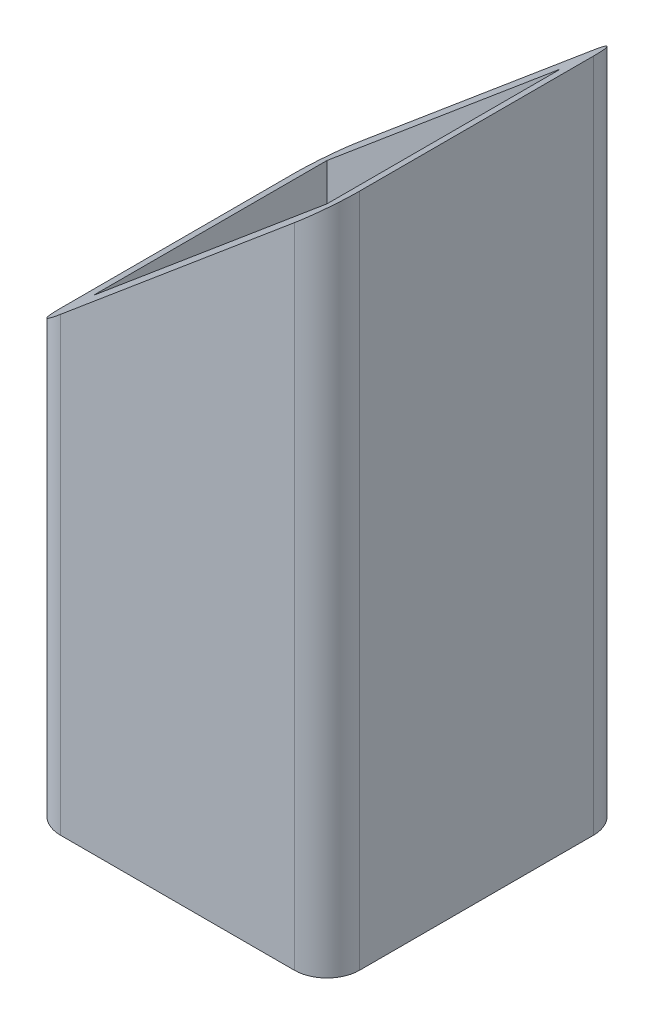
SolidWorks part; units mm, degrees
material "Plain Carbon Steel"
ref_plane "Front Plane" through (0, 0, 0) normal (0, 0, 1) x (1, 0, 0)
ref_plane "Top Plane" through (0, 0, 0) normal (0, 1, 0) x (1, 0, 0)
ref_plane "Right Plane" through (0, 0, 0) normal (1, 0, 0) x (0, 0, -1)
sketch "Sketch1" plane through (0, 0, 0) normal (0, 1, 0) x (1, 0, 0)
  line L1 (2.8, 0) -> (22.8, 0)
  line L2 (0, -2.8) -> (0, -22.8)
  line L3 (2.8, -25.6) -> (22.8, -25.6)
  line L4 (25.6, -2.8) -> (25.6, -22.8)
  arc A0 (22.8, 0) -> (25.6, -2.8) centre (22.8, -2.8) cw
  arc A1 (22.8, -25.6) -> (25.6, -22.8) centre (22.8, -22.8) ccw
  arc A2 (0, -22.8) -> (2.8, -25.6) centre (2.8, -22.8) ccw
  arc A3 (2.8, 0) -> (0, -2.8) centre (2.8, -2.8) ccw
  point P7 (25.6, 0)
  point P10 (25.6, -25.6)
  point P15 (0, 0)
  dimension "D2" = 2.8
  dimension "D1" = 25.6
extrude "Boss-Extrude1" add sketch "Sketch1" along normal blind 60
sketch "Sketch3" plane through (0, 0, 0) normal (0, -1, 0) x (-1, 0, 0)
  line L4 (-2.8, -2.8) -> (-22.8, -2.8)
  line L5 (-2.8, -2.8) -> (-2.8, -22.8)
  line L6 (-2.8, -22.8) -> (-22.8, -22.8)
  line L7 (-22.8, -2.8) -> (-22.8, -22.8)
  line L8 (-2.8, -2.8) -> (-22.8, -22.8) construction
  line L9 (-2.8, -22.8) -> (-22.8, -2.8) construction
  point P6 (-12.8, -12.8)
extrude "Cut-Extrude1" cut sketch "Sketch3" against normal blind 1040.5
sketch "Sketch4" plane through (0, 0, 25.6) normal (0, 0, 1) x (1, 0, 0)
  line L0 (-0.9867, 35.4016) -> (-0.9867, 60)
  line L1 (-0.9867, 35.4016) -> (27.022, 58.9113)
  line L2 (-0.9867, 60) -> (27.022, 60)
  line L3 (27.022, 60) -> (27.022, 58.9113)
extrude "Cut-Extrude2" cut sketch "Sketch4" against normal up to surface (25.6 mm away) up to face at (12.8, 30, 0)
